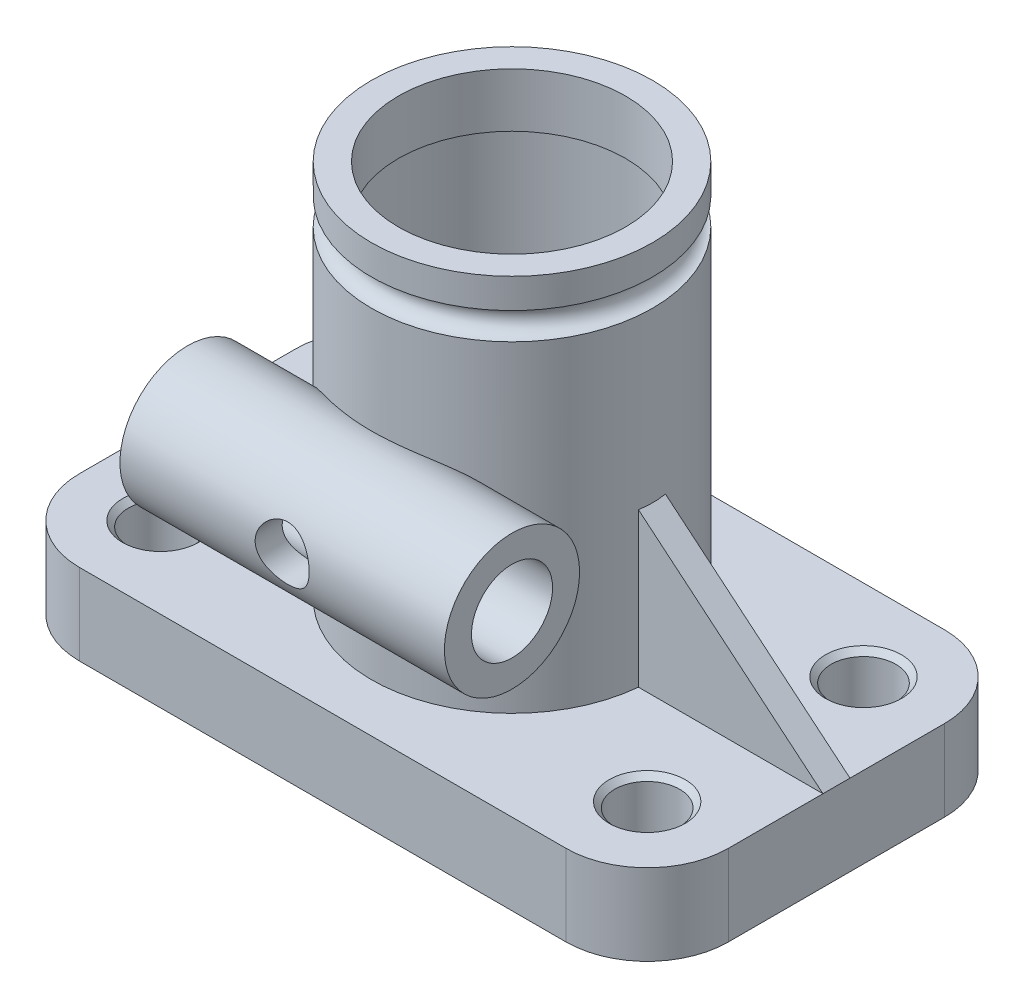
SolidWorks part; units mm, degrees
ref_plane "Front Plane" through (0, 0, 0) normal (0, 0, 1) x (1, 0, 0)
ref_plane "Top Plane" through (0, 0, 0) normal (0, 1, 0) x (1, 0, 0)
ref_plane "Right Plane" through (0, 0, 0) normal (1, 0, 0) x (0, 0, -1)
sketch "Sketch1" plane through (0, 0, 0) normal (0, 1, 0) x (1, 0, 0)
  line L1 (-60, 35) -> (60, 35)
  line L2 (-60, 35) -> (-60, -35)
  line L3 (-60, -35) -> (60, -35)
  line L4 (60, 35) -> (60, -35)
  line L5 (-60, 35) -> (60, -35) construction
  line L6 (-60, -35) -> (60, 35) construction
  point P0 (0, 0)
  dimension "D1" = 120
  dimension "D2" = 70
extrude "Boss-Extrude1" add sketch "Sketch1" along normal blind 15 contours L1 L4 L3 L2
sketch "Sketch2" plane through (0, 15, 0) normal (0, 1, 0) x (1, 0, 0)
  circle A0 centre (0, 0) radius 26
  dimension "D1" = 52
extrude "Boss-Extrude2" add sketch "Sketch2" along normal blind 70
sketch "Sketch7" plane through (0, 0, 0) normal (0, 0, 1) x (1, 0, 0)
  line L0 (0, 0) -> (0, 85)
  line L1 (26, 85) -> (-26, 85) construction
  line L2 (0, 85) -> (21, 85)
  line L3 (21, 85) -> (21, 65)
  line L4 (21, 65) -> (23, 65)
  line L5 (23, 65) -> (23, 15)
  line L6 (-60, 15) -> (60, 15) construction
  line L7 (23, 15) -> (15, 15)
  line L8 (15, 15) -> (15, 10)
  line L9 (15, 10) -> (12, 10)
  line L10 (12, 10) -> (12, 0)
  line L11 (-60, 0) -> (60, 0) construction
  line L12 (12, 0) -> (0, 0)
  dimension "D1" = 21
  dimension "D2" = 23
  dimension "D3" = 65
  dimension "D4" = 5
  dimension "D5" = 15
  dimension "D6" = 12
revolve "Cut-Revolve2" cut sketch "Sketch7" angle 360 about L0
sketch "Sketch8" plane through (0, 0, 0) normal (0, 0, 1) x (1, 0, 0)
  line L0 (26, 15) -> (26, 85) construction
  line L1 (26, 85) -> (-26, 85) construction
  line L2 (0, 0) -> (0, 71.6685) construction
  circle A0 centre (26, 77) radius 2.5
  dimension "D1" = 5
  dimension "D2" = 8
revolve "Cut-Revolve3" cut sketch "Sketch8" angle 360 about L2
sketch "Sketch9" plane through (0, 0, 0) normal (0, 0, 1) x (1, 0, 0)
  line L0 (24, 45) -> (60, 15)
  line L2 (24, 45) -> (24, 15)
  line L3 (-60, 15) -> (60, 15) construction
  line L4 (24, 15) -> (60, 15)
  line L5 (-60, 0) -> (60, 0) construction
  dimension "D1" = 24
  dimension "D2" = 45
extrude "Boss-Extrude3" add sketch "Sketch9" along normal mid plane 5
ref_plane "Plane1" through (30, 0, 0) normal (1, 0, 0) x (0, 0, -1)
sketch "Sketch10" plane through (30, 0, 0) normal (1, 0, 0) x (0, 0, -1)
  line L0 (-2.5, 15) -> (-35, 15) construction
  circle A0 centre (-30, 43) radius 12.5
  dimension "D1" = 25
  dimension "D2" = 28
  dimension "D3" = 30
extrude "Boss-Extrude4" add sketch "Sketch10" against normal blind 60
sketch "Sketch11" plane through (0, 15, 0) normal (0, 1, 0) x (1, 0, 0)
  circle A0 centre (0, 0) radius 23 construction
  circle A1 centre (0, 0) radius 23
extrude "Cut-Extrude1" cut sketch "Sketch11" along normal blind 60
hole_wizard "Hole2" positions "Sketch12" profile "Sketch13" legacy end condition through all
sketch "Sketch12" plane through (30, 0, 0) normal (1, 0, 0) x (0, 0, -1)
  point P0 (-30, 43)
sketch "Sketch13" plane through (30, 43, 30) normal (0, 1, 0) x (0, 0, -1)
  line L0 (0, 0) -> (0, 90)
  line L1 (0, 90) -> (7.5, 90)
  line L2 (7.5, 90) -> (7.5, 0)
  line L3 (7.5, 0) -> (0, 0)
  line L4 (0, 110) -> (0, -10) construction
  dimension "Diameter" = 15
  dimension "Depth" = 90
sketch "Sketch14" plane through (0, 0, 0) normal (0, 0, 1) x (1, 0, 0)
  line L1 (-60, 15) -> (60, 15) construction
  circle A0 centre (0, 43) radius 5
  point P5 (0, 0)
  dimension "D1" = 10
  dimension "D2" = 28
extrude "Cut-Extrude2" cut sketch "Sketch14" along normal blind 60
fillet "Fillet1" radius 15 4 edges at (60, 7.5, 35) (60, 7.5, -35) (-60, 7.5, -35) (-60, 7.5, 35)
hole_wizard "M14 Tapped Hole1" positions "Sketch17" profile "Sketch18" tap size "M14" standard "ISO" end condition through all
sketch "Sketch17" plane through (0, 15, 0) normal (0, 1, 0) x (1, 0, 0)
  point P0 (45, -20)
  point P3 (45, 20)
  point P6 (-45, 20)
  point P9 (-45, -20)
sketch "Sketch18" plane through (45, 15, 20) normal (1, 0, 0) x (0, 0, 1)
  line L0 (0, 0) -> (0, 15)
  line L1 (0, 15) -> (6, 15)
  line L2 (6, 15) -> (6, 1.025)
  line L3 (6, 1.025) -> (7.025, 0)
  line L5 (7.025, 0) -> (0, 0)
  line L6 (-6, 1.025) -> (-7.025, 0) construction
  line L11 (0, -6.35) -> (0, 107.95) construction
  dimension "Thru Tap Drill Dia." = 12
  dimension "Thru Tap Drill Depth" = 15
  dimension "Near C'Sink Dia." = 14.05
  dimension "Near C'Sink Angle" = 90
cosmetic thread "Hole Thread1" parameters "D2"=14
cosmetic thread "Hole Thread2" parameters "D2"=14
cosmetic thread "Hole Thread3" parameters "D2"=14
cosmetic thread "Hole Thread4" parameters "D2"=14
